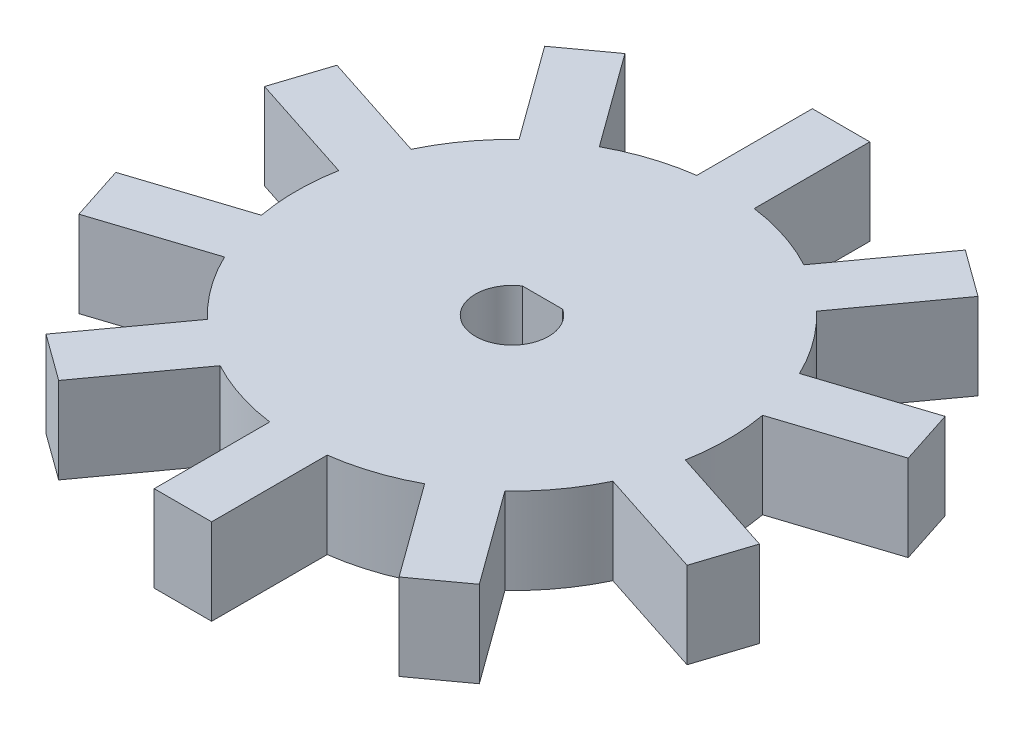
SolidWorks part; units mm, degrees
ref_plane "Front Plane" through (0, 0, 0) normal (0, 0, 1) x (1, 0, 0)
ref_plane "Top Plane" through (0, 0, 0) normal (0, 1, 0) x (1, 0, 0)
ref_plane "Right Plane" through (0, 0, 0) normal (1, 0, 0) x (0, 0, -1)
sketch "Sketch1" plane through (0, 0, 0) normal (0, 1, 0) x (1, 0, 0)
  line L0 (-2, 22.9129) -> (-2, 14.8661)
  line L1 (2, 22.9129) -> (2, 14.8661)
  line L2 (-2, 22.9129) -> (2, 22.9129)
  line L3 (11.8498, 19.7125) -> (7.12, 13.2025)
  line L4 (11.8498, 19.7125) -> (15.0859, 17.3613)
  line L5 (15.0859, 17.3613) -> (10.3561, 10.8513)
  line L6 (21.1734, 8.9826) -> (13.5204, 6.496)
  line L7 (21.1734, 8.9826) -> (22.4095, 5.1784)
  line L8 (22.4095, 5.1784) -> (14.7565, 2.6918)
  line L9 (22.4095, -5.1784) -> (14.7565, -2.6918)
  line L10 (22.4095, -5.1784) -> (21.1734, -8.9826)
  line L11 (21.1734, -8.9826) -> (13.5204, -6.496)
  line L12 (15.0859, -17.3613) -> (10.3561, -10.8513)
  line L13 (15.0859, -17.3613) -> (11.8498, -19.7125)
  line L14 (11.8498, -19.7125) -> (7.12, -13.2025)
  line L15 (2, -22.9129) -> (2, -14.8661)
  line L16 (2, -22.9129) -> (-2, -22.9129)
  line L17 (-2, -22.9129) -> (-2, -14.8661)
  line L18 (-11.8498, -19.7125) -> (-7.12, -13.2025)
  line L19 (-11.8498, -19.7125) -> (-15.0859, -17.3613)
  line L20 (-15.0859, -17.3613) -> (-10.3561, -10.8513)
  line L21 (-21.1734, -8.9826) -> (-13.5204, -6.496)
  line L22 (-21.1734, -8.9826) -> (-22.4095, -5.1784)
  line L23 (-22.4095, -5.1784) -> (-14.7565, -2.6918)
  line L24 (-22.4095, 5.1784) -> (-14.7565, 2.6918)
  line L25 (-22.4095, 5.1784) -> (-21.1734, 8.9826)
  line L26 (-21.1734, 8.9826) -> (-13.5204, 6.496)
  line L27 (-15.0859, 17.3613) -> (-10.3561, 10.8513)
  line L28 (-15.0859, 17.3613) -> (-11.8498, 19.7125)
  line L29 (-11.8498, 19.7125) -> (-7.12, 13.2025)
  circle A0 centre (0, 0) radius 23
  circle A1 centre (0, 0) radius 15
  arc A2 (-2, 22.9129) -> (2, 22.9129) centre (0, 0) cw
  point P47 (0, 0)
  dimension "D1" = 46
  dimension "D2" = 30
  dimension "D3" = 4
  dimension "D4" = 10
extrude "Boss-Extrude1" add sketch "Sketch1" along normal blind 6 contours A1 L29 L28 L27 | A1 L1 L2 L0 | A1 L5 L4 L3 | A1 L8 L7 L6 | A1 | A1 L11 L10 L9 | A1 L14 L13 L12 | A1 L17 L16 L15 | A1 L20 L19 L18 | A1 L23 L22 L21 | A1 L26 L25 L24
sketch "Sketch2" plane through (0, 6, 0) normal (0, 1, 0) x (1, 0, 0)
  line L0 (-1.402, 2.13) -> (1.402, 2.13)
  circle A0 centre (0, 0) radius 2.55
  dimension "D1" = 5.1
  dimension "D2" = 2.13
extrude "Cut-Extrude1" cut sketch "Sketch2" against normal blind 6 contours L0 A0
